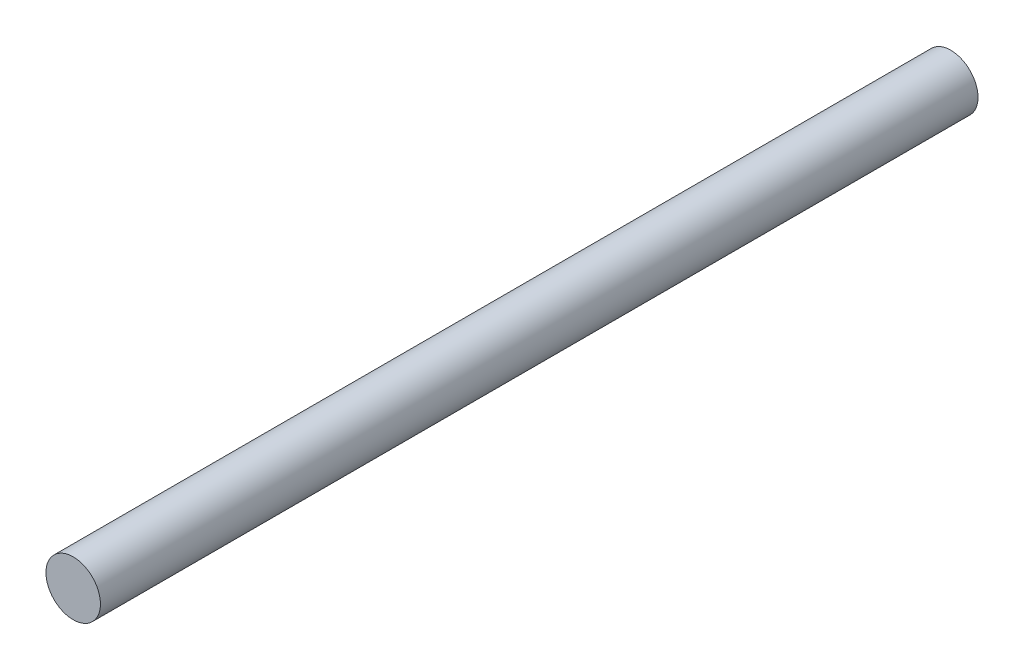
SolidWorks part; units mm, degrees
ref_plane "Front Plane" through (0, 0, 0) normal (0, 0, 1) x (1, 0, 0)
ref_plane "Top Plane" through (0, 0, 0) normal (0, 1, 0) x (1, 0, 0)
ref_plane "Right Plane" through (0, 0, 0) normal (1, 0, 0) x (0, 0, -1)
sketch "Sketch1" plane through (0, 0, 0) normal (0, 0, 1) x (1, 0, 0)
  circle A0 centre (0, 0) radius 8.89
  dimension "D1" = 17.78
extrude "Boss-Extrude1" add sketch "Sketch1" along normal blind 3.2 and the other way blind 283.2
